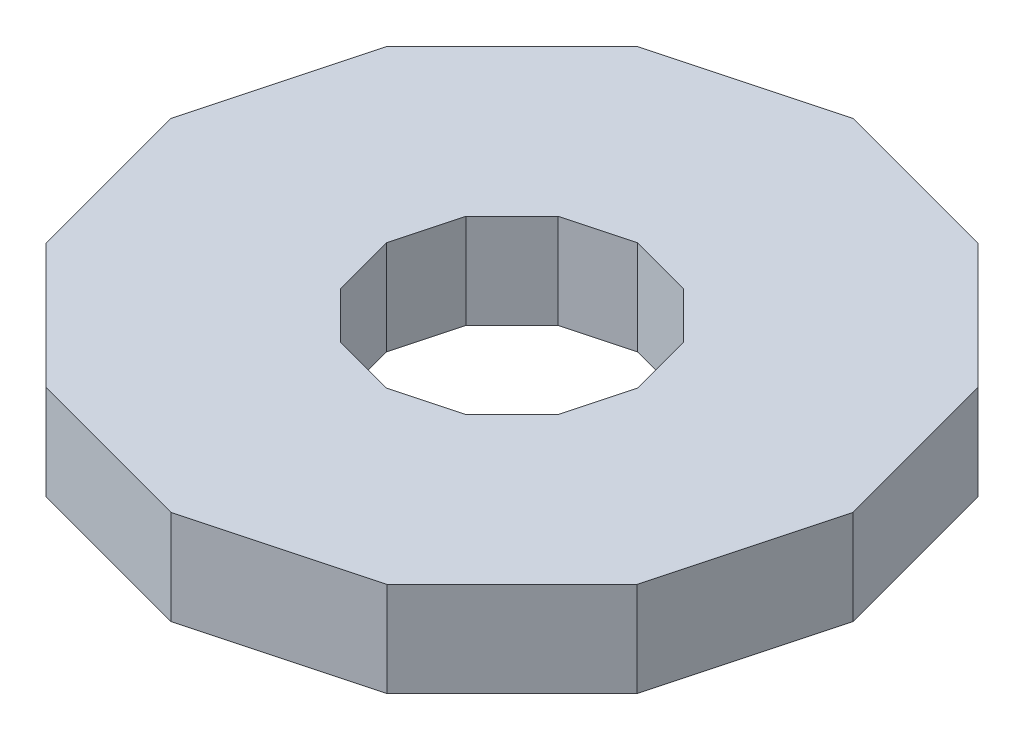
SolidWorks part; units mm, degrees
ref_plane "Front Plane" through (0, 0, 0) normal (0, 0, 1) x (1, 0, 0)
ref_plane "Top Plane" through (0, 0, 0) normal (0, 1, 0) x (1, 0, 0)
ref_plane "Right Plane" through (0, 0, 0) normal (1, 0, 0) x (0, 0, -1)
sketch "Sketch1" plane through (0, 0, 0) normal (0, 1, 0) x (1, 0, 0)
  line L0 (0, 0) -> (25.3082, 0) construction
  line L1 (68.6966, 0) -> (59.493, 34.3483)
  line L2 (59.493, 34.3483) -> (34.3483, 59.493)
  line L3 (34.3483, 59.493) -> (0, 68.6966)
  line L4 (0, 68.6966) -> (-34.3483, 59.493)
  line L5 (-34.3483, 59.493) -> (-59.493, 34.3483)
  line L6 (-59.493, 34.3483) -> (-68.6966, 0)
  line L7 (-68.6966, 0) -> (-59.493, -34.3483)
  line L8 (-59.493, -34.3483) -> (-34.3483, -59.493)
  line L9 (-34.3483, -59.493) -> (0, -68.6966)
  line L10 (0, -68.6966) -> (34.3483, -59.493)
  line L11 (34.3483, -59.493) -> (59.493, -34.3483)
  line L12 (59.493, -34.3483) -> (68.6966, 0)
  line L13 (25.3082, 0) -> (21.9176, 12.6541)
  line L14 (21.9176, 12.6541) -> (12.6541, 21.9176)
  line L15 (12.6541, 21.9176) -> (0, 25.3082)
  line L16 (0, 25.3082) -> (-12.6541, 21.9176)
  line L17 (-12.6541, 21.9176) -> (-21.9176, 12.6541)
  line L18 (-21.9176, 12.6541) -> (-25.3082, 0)
  line L19 (-25.3082, 0) -> (-21.9176, -12.6541)
  line L20 (-21.9176, -12.6541) -> (-12.6541, -21.9176)
  line L21 (-12.6541, -21.9176) -> (0, -25.3082)
  line L22 (0, -25.3082) -> (12.6541, -21.9176)
  line L23 (12.6541, -21.9176) -> (21.9176, -12.6541)
  line L24 (21.9176, -12.6541) -> (25.3082, 0)
  circle A0 centre (0, 0) radius 66.3559 construction
  circle A1 centre (0, 0) radius 24.4459 construction
  dimension "D1" = 41.91
  dimension "D2" = 35.56
extrude "Boss-Extrude1" add sketch "Sketch1" along normal blind 19.05
